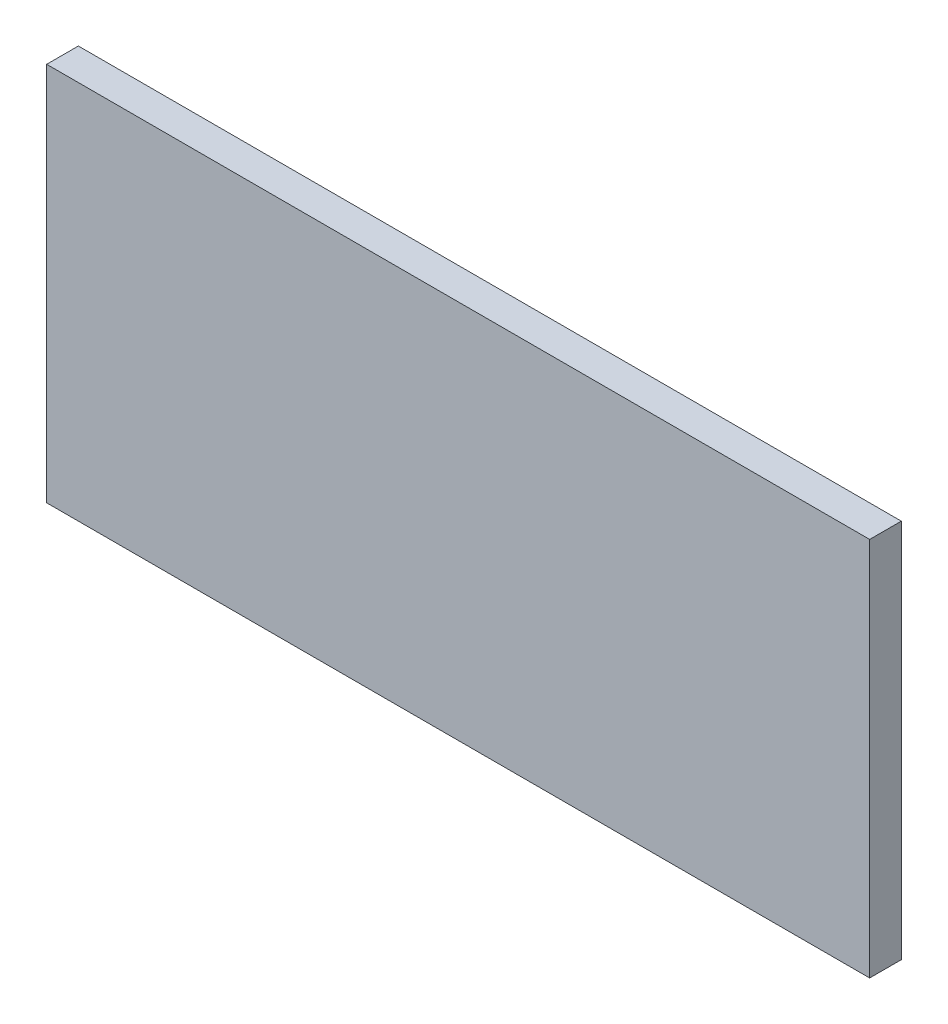
SolidWorks part; units mm, degrees
ref_plane "Front Plane" through (0, 0, 0) normal (0, 0, 1) x (1, 0, 0)
ref_plane "Top Plane" through (0, 0, 0) normal (0, 1, 0) x (1, 0, 0)
ref_plane "Right Plane" through (0, 0, 0) normal (1, 0, 0) x (0, 0, -1)
sketch "Sketch1" plane through (0, 0, 0) normal (0, 0, 1) x (1, 0, 0)
  line L1 (-82.55, -38.1) -> (82.55, -38.1)
  line L2 (-82.55, -38.1) -> (-82.55, 38.1)
  line L3 (-82.55, 38.1) -> (82.55, 38.1)
  line L4 (82.55, -38.1) -> (82.55, 38.1)
  line L5 (-82.55, -38.1) -> (82.55, 38.1) construction
  line L6 (-82.55, 38.1) -> (82.55, -38.1) construction
  point P0 (0, 0)
  dimension "D1" = 165.1
  dimension "D2" = 76.2
extrude "Boss-Extrude1" add sketch "Sketch1" along normal blind 6.35
equation "\"top-panel-width\"= 6.5in"
equation "\"top-panel-height\"= 3in"
equation "\"material-thickness\"= .25in"
equation "\"D1@Sketch1\"=\"top-panel-width\""
equation "\"D2@Sketch1\"=\"top-panel-height\""
equation "\"D1@Boss-Extrude1\"=\"material-thickness\""
